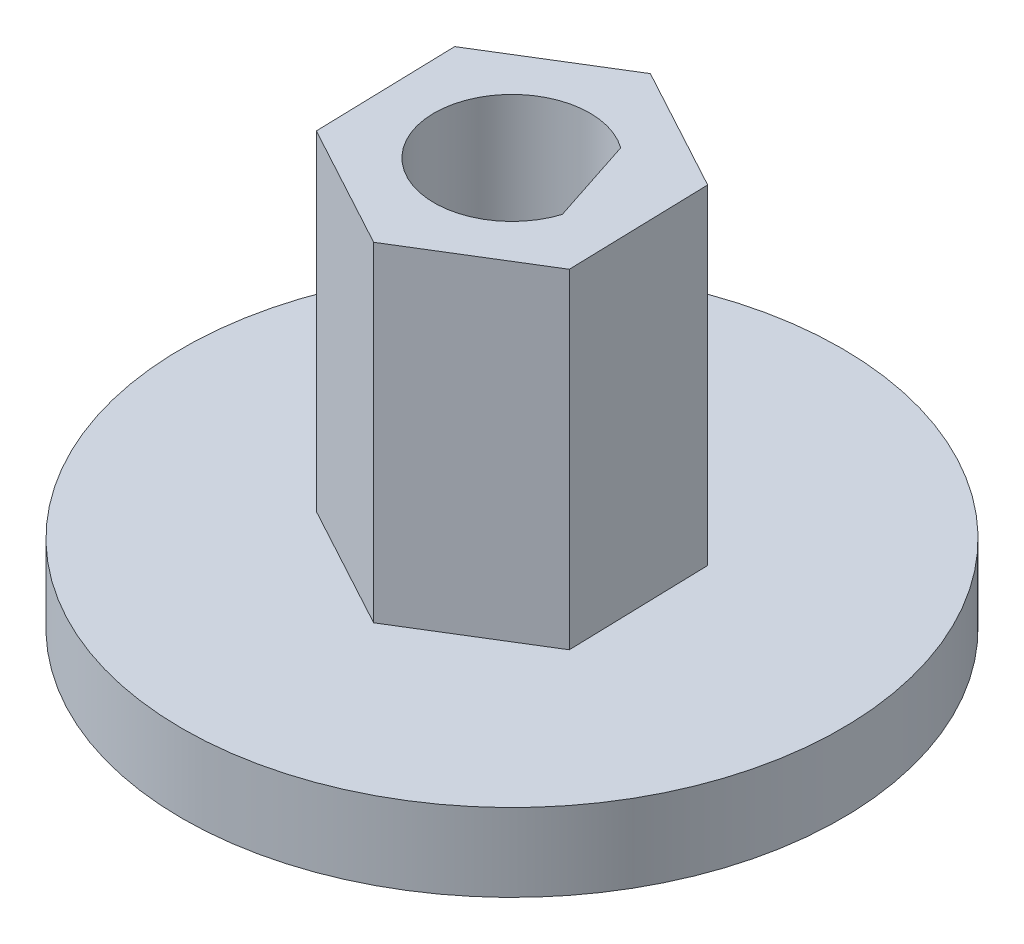
SolidWorks part; units mm, degrees
ref_plane "Front" through (0, 0, 0) normal (0, 0, 1) x (1, 0, 0)
ref_plane "Top" through (0, 0, 0) normal (0, 1, 0) x (1, 0, 0)
ref_plane "Right" through (0, 0, 0) normal (1, 0, 0) x (0, 0, -1)
sketch "Sketch1" plane through (0, 0, 0) normal (0, 1, 0) x (1, 0, 0)
  circle A0 centre (0, 0) radius 12.7
  dimension "D1" = 25.4
extrude "Boss-Extrude1" add sketch "Sketch1" along normal blind 3
sketch "Sketch2" plane through (0, 3, 0) normal (0, 1, 0) x (1, 0, 0)
  line L1 (0.1489, -5.48) -> (4.8203, -2.6111)
  line L2 (4.8203, -2.6111) -> (4.6714, 2.8689)
  line L3 (4.6714, 2.8689) -> (-0.1489, 5.48)
  line L4 (-0.1489, 5.48) -> (-4.8203, 2.6111)
  line L5 (-4.8203, 2.6111) -> (-4.6714, -2.8689)
  line L6 (-4.6714, -2.8689) -> (0.1489, -5.48)
  circle A0 centre (0, 0) radius 4.7476 construction
  dimension "D1" = 5.48
extrude "Boss-Extrude2" add sketch "Sketch2" along normal blind 12.7
sketch "Sketch6" plane through (0, 15.7, 0) normal (0, 1, 0) x (1, 0, 0)
  line L0 (1.758, 2.431) -> (2.8558, -0.919)
  circle A0 centre (0, 0) radius 3
  dimension "D1" = 3.35
extrude "Cut-Extrude1" cut sketch "Sketch6" against normal blind 23 contours L0 A0
